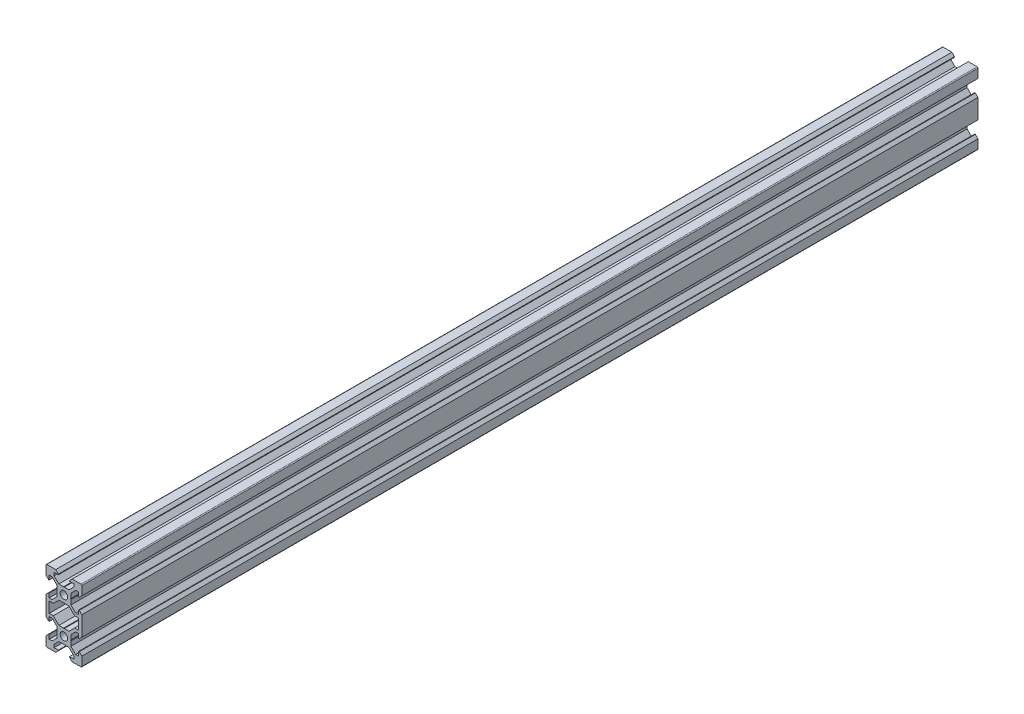
SolidWorks part; units mm, degrees
ref_plane "Front Plane" through (0, 0, 0) normal (0, 0, 1) x (1, 0, 0)
ref_plane "Top Plane" through (0, 0, 0) normal (0, 1, 0) x (1, 0, 0)
ref_plane "Right Plane" through (0, 0, 0) normal (1, 0, 0) x (0, 0, -1)
sketch "Sketch1" plane through (0, 0, 0) normal (0, 0, 1) x (1, 0, 0)
  line L0 (0, 0) -> (0, 20243.958) construction
  line L1 (0, 0) -> (20243.958, 0) construction
  line L2 (-10, 0) -> (10, 20) construction
  line L3 (-10, -20) -> (10, -20) construction
  line L4 (-10, -20) -> (-10, 20) construction
  line L5 (-10, 20) -> (10, 20) construction
  line L6 (10, -20) -> (10, 20) construction
  line L7 (0, 20) -> (0, -20) construction
  line L8 (-10, 0) -> (10, 0) construction
  line L9 (10, 0) -> (-10, 20) construction
  line L10 (10, 0) -> (-10, -20) construction
  line L11 (10, -20) -> (-10, 0) construction
  line L12 (10, 10) -> (-10, 10) construction
  line L14 (2.8393, 13.9) -> (5.5, 16.5607)
  line L15 (5.5, 16.5607) -> (5.5, 18.2)
  line L16 (5.5, 18.2) -> (3.125, 18.2)
  line L17 (3.125, 18.2) -> (3.125, 18.545)
  line L18 (3.125, 18.545) -> (4.58, 20)
  line L19 (4.58, 20) -> (10, 20)
  line L20 (10, 20) -> (10, 14.58)
  line L21 (10, 14.58) -> (8.545, 13.125)
  line L22 (8.545, 13.125) -> (8.2, 13.125)
  line L23 (8.2, 13.125) -> (8.2, 15.5)
  line L24 (8.2, 15.5) -> (6.5607, 15.5)
  line L25 (6.5607, 15.5) -> (3.9, 12.8393)
  line L26 (0, 13.7) -> (0.2, 13.9)
  line L27 (0.2, 13.9) -> (2.8393, 13.9)
  line L28 (3.9, 12.8393) -> (3.9, 10.2)
  line L29 (3.9, 10.2) -> (3.7, 10)
  line L30 (3.7, 10) -> (3.9, 9.8)
  line L31 (3.9, 9.8) -> (3.9, 7.1607)
  line L32 (3.9, 7.1607) -> (6.5607, 4.5)
  line L33 (6.5607, 4.5) -> (8.2, 4.5)
  line L34 (8.2, 4.5) -> (8.2, 6.875)
  line L35 (8.2, 6.875) -> (8.545, 6.875)
  line L36 (8.545, 6.875) -> (10, 5.42)
  line L37 (10, 5.42) -> (10, -5.42)
  line L38 (8.2, -3) -> (8.2, 3)
  line L39 (8.2, 3) -> (5.9393, 3)
  line L40 (5.9393, 3) -> (2.8393, 6.1)
  line L41 (2.8393, 6.1) -> (0.2, 6.1)
  line L42 (0.2, 6.1) -> (0, 6.3)
  line L43 (-5.9393, 3) -> (-2.8393, 6.1)
  line L44 (-0.2, 6.1) -> (0, 6.3)
  line L45 (-2.8393, 6.1) -> (-0.2, 6.1)
  line L46 (-8.2, 3) -> (-5.9393, 3)
  line L47 (-8.2, -3) -> (-8.2, 3)
  line L48 (-10, 5.42) -> (-10, -5.42)
  line L49 (-8.545, 6.875) -> (-10, 5.42)
  line L50 (-8.2, 4.5) -> (-8.2, 6.875)
  line L51 (-6.5607, 4.5) -> (-8.2, 4.5)
  line L52 (-8.2, 6.875) -> (-8.545, 6.875)
  line L53 (-3.9, 7.1607) -> (-6.5607, 4.5)
  line L54 (-3.9, 9.8) -> (-3.9, 7.1607)
  line L55 (-3.7, 10) -> (-3.9, 9.8)
  line L56 (-3.9, 10.2) -> (-3.7, 10)
  line L57 (-3.9, 12.8393) -> (-3.9, 10.2)
  line L58 (-6.5607, 15.5) -> (-3.9, 12.8393)
  line L59 (-8.2, 15.5) -> (-6.5607, 15.5)
  line L60 (-8.2, 13.125) -> (-8.2, 15.5)
  line L61 (-8.545, 13.125) -> (-8.2, 13.125)
  line L62 (-10, 14.58) -> (-8.545, 13.125)
  line L63 (-10, 20) -> (-10, 14.58)
  line L64 (-4.58, 20) -> (-10, 20)
  line L65 (-3.125, 18.545) -> (-4.58, 20)
  line L66 (-3.125, 18.2) -> (-3.125, 18.545)
  line L67 (-5.5, 18.2) -> (-3.125, 18.2)
  line L68 (-5.5, 16.5607) -> (-5.5, 18.2)
  line L69 (-2.8393, 13.9) -> (-5.5, 16.5607)
  line L70 (-0.2, 13.9) -> (-2.8393, 13.9)
  line L71 (0, 13.7) -> (-0.2, 13.9)
  line L72 (10, -10) -> (-10, -10) construction
  line L73 (10, 0) -> (-10, -20) construction
  line L74 (-10, -20) -> (10, -20) construction
  line L75 (-10, 0) -> (10, -20) construction
  line L76 (0, -13.7) -> (-0.2, -13.9)
  line L77 (-0.2, -13.9) -> (-2.8393, -13.9)
  line L78 (-2.8393, -13.9) -> (-5.5, -16.5607)
  line L79 (-5.5, -16.5607) -> (-5.5, -18.2)
  line L80 (-5.5, -18.2) -> (-3.125, -18.2)
  line L81 (-3.125, -18.2) -> (-3.125, -18.545)
  line L82 (-3.125, -18.545) -> (-4.58, -20)
  line L83 (-4.58, -20) -> (-10, -20)
  line L84 (-10, -20) -> (-10, -14.58)
  line L85 (-10, -14.58) -> (-8.545, -13.125)
  line L86 (-8.545, -13.125) -> (-8.2, -13.125)
  line L87 (-8.2, -13.125) -> (-8.2, -15.5)
  line L88 (-8.2, -15.5) -> (-6.5607, -15.5)
  line L89 (-6.5607, -15.5) -> (-3.9, -12.8393)
  line L90 (-3.9, -12.8393) -> (-3.9, -10.2)
  line L91 (-3.9, -10.2) -> (-3.7, -10)
  line L92 (-3.7, -10) -> (-3.9, -9.8)
  line L93 (-3.9, -9.8) -> (-3.9, -7.1607)
  line L94 (-3.9, -7.1607) -> (-6.5607, -4.5)
  line L95 (-8.2, -6.875) -> (-8.545, -6.875)
  line L96 (-6.5607, -4.5) -> (-8.2, -4.5)
  line L97 (-8.2, -4.5) -> (-8.2, -6.875)
  line L98 (-8.545, -6.875) -> (-10, -5.42)
  line L99 (-8.2, -3) -> (-5.9393, -3)
  line L100 (-2.8393, -6.1) -> (-0.2, -6.1)
  line L101 (-0.2, -6.1) -> (0, -6.3)
  line L102 (-5.9393, -3) -> (-2.8393, -6.1)
  line L103 (0.2, -6.1) -> (0, -6.3)
  line L104 (2.8393, -6.1) -> (0.2, -6.1)
  line L105 (5.9393, -3) -> (2.8393, -6.1)
  line L106 (8.2, -3) -> (5.9393, -3)
  line L107 (8.545, -6.875) -> (10, -5.42)
  line L108 (8.2, -6.875) -> (8.545, -6.875)
  line L109 (8.2, -4.5) -> (8.2, -6.875)
  line L110 (6.5607, -4.5) -> (8.2, -4.5)
  line L111 (3.9, -7.1607) -> (6.5607, -4.5)
  line L112 (3.9, -9.8) -> (3.9, -7.1607)
  line L113 (3.7, -10) -> (3.9, -9.8)
  line L114 (3.9, -10.2) -> (3.7, -10)
  line L115 (3.9, -12.8393) -> (3.9, -10.2)
  line L116 (0.2, -13.9) -> (2.8393, -13.9)
  line L117 (0, -13.7) -> (0.2, -13.9)
  line L118 (6.5607, -15.5) -> (3.9, -12.8393)
  line L119 (8.2, -15.5) -> (6.5607, -15.5)
  line L120 (8.2, -13.125) -> (8.2, -15.5)
  line L121 (8.545, -13.125) -> (8.2, -13.125)
  line L122 (10, -14.58) -> (8.545, -13.125)
  line L123 (10, -20) -> (10, -14.58)
  line L124 (4.58, -20) -> (10, -20)
  line L125 (3.125, -18.545) -> (4.58, -20)
  line L126 (3.125, -18.2) -> (3.125, -18.545)
  line L127 (5.5, -18.2) -> (3.125, -18.2)
  line L128 (5.5, -16.5607) -> (5.5, -18.2)
  line L129 (2.8393, -13.9) -> (5.5, -16.5607)
  circle A0 centre (0, 10) radius 2.1
  circle A1 centre (0, -10) radius 2.1
  point P5 (0, 0)
  point P101 (-8.2, 0)
  point P109 (8.2, 0)
  dimension "D15" = 4.2
  dimension "D1" = 40
  dimension "D2" = 20
  dimension "D3" = 4.58
  dimension "D4" = 1.8
  dimension "D5" = 3.125
  dimension "D6" = 135
  dimension "D7" = 1.5
  dimension "D8" = 4.3
  dimension "D9" = 0.2
  dimension "D10" = 0.2
  dimension "D11" = 5.5
  dimension "D12" = 135
  dimension "D13" = 1.5
  dimension "D14" = 1.5
extrude "Boss-Extrude1" add sketch "Sketch1" along normal blind 500
fillet "Fillet1" radius 0.5 4 edges at (-10, -20, 250) (10, -20, 250) (-10, 20, 250) (10, 20, 250)
